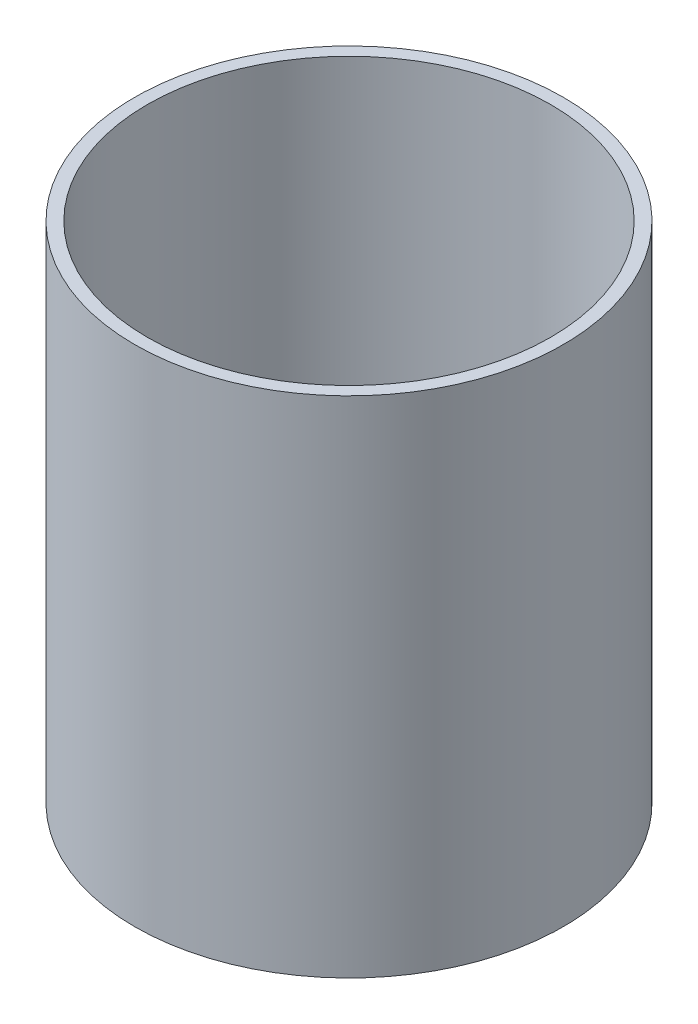
SolidWorks part; units mm, degrees
ref_plane "Front Plane" through (0, 0, 0) normal (0, 0, 1) x (1, 0, 0)
ref_plane "Top Plane" through (0, 0, 0) normal (0, 1, 0) x (1, 0, 0)
ref_plane "Right Plane" through (0, 0, 0) normal (1, 0, 0) x (0, 0, -1)
sketch "Sketch1" plane through (0, 0, 0) normal (0, 1, 0) x (1, 0, 0)
  circle A0 centre (0, 0) radius 101.6
  circle A1 centre (0, 0) radius 107.95
extrude "Boss-Extrude1" add sketch "Sketch1" along normal blind 254
